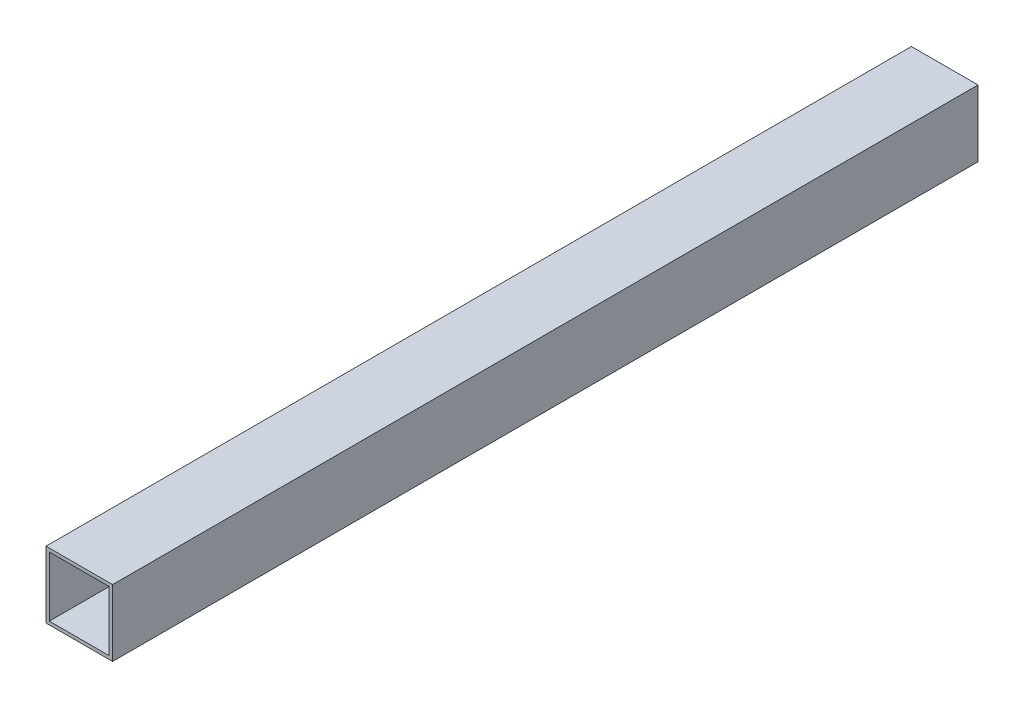
SolidWorks part; units mm, degrees
ref_plane "前视基准面" through (0, 0, 0) normal (0, 0, 1) x (1, 0, 0)
ref_plane "上视基准面" through (0, 0, 0) normal (0, 1, 0) x (1, 0, 0)
ref_plane "右视基准面" through (0, 0, 0) normal (1, 0, 0) x (0, 0, -1)
sketch "草图1" plane through (0, 0, 0) normal (0, 0, 1) x (1, 0, 0)
  line L0 (-9, 9) -> (9, 9)
  line L1 (-10, -10) -> (10, -10)
  line L2 (-10, -10) -> (-10, 10)
  line L3 (-10, 10) -> (10, 10)
  line L4 (10, -10) -> (10, 10)
  line L5 (-10, -10) -> (10, 10) construction
  line L6 (-10, 10) -> (10, -10) construction
  line L7 (9, -9) -> (9, 9)
  line L8 (-9, -9) -> (9, -9)
  line L9 (-9, -9) -> (-9, 9)
  point P0 (0, 0)
  dimension "D1" = 20
  dimension "D2" = 20
  dimension "D3" = 1
extrude "凸台-拉伸1" add sketch "草图1" along normal blind 260
